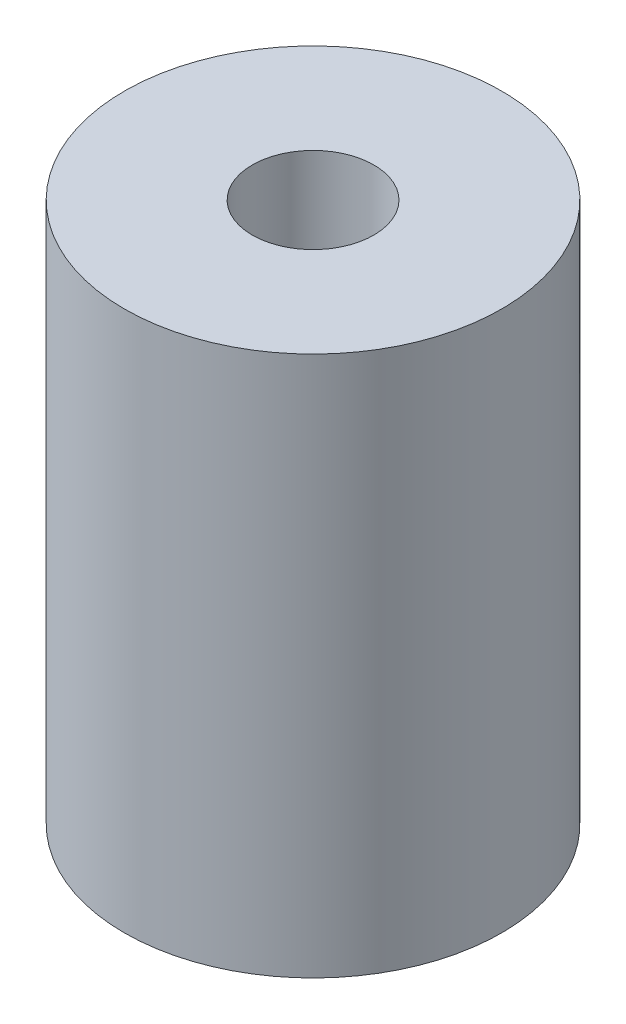
SolidWorks part; units mm, degrees
material "Brass"
ref_plane "Front Plane" through (0, 0, 0) normal (0, 0, 1) x (1, 0, 0)
ref_plane "Top Plane" through (0, 0, 0) normal (0, 1, 0) x (1, 0, 0)
ref_plane "Right Plane" through (0, 0, 0) normal (1, 0, 0) x (0, 0, -1)
sketch "Sketch2" plane through (0, 0, 0) normal (0, 1, 0) x (1, 0, 0)
  circle A0 centre (0, 0) radius 2.25
  circle A1 centre (0, 0) radius 6.985
  dimension "D1" = 4.5
  dimension "D2" = 13.97
extrude "Boss-Extrude3" add sketch "Sketch2" along normal blind 20
